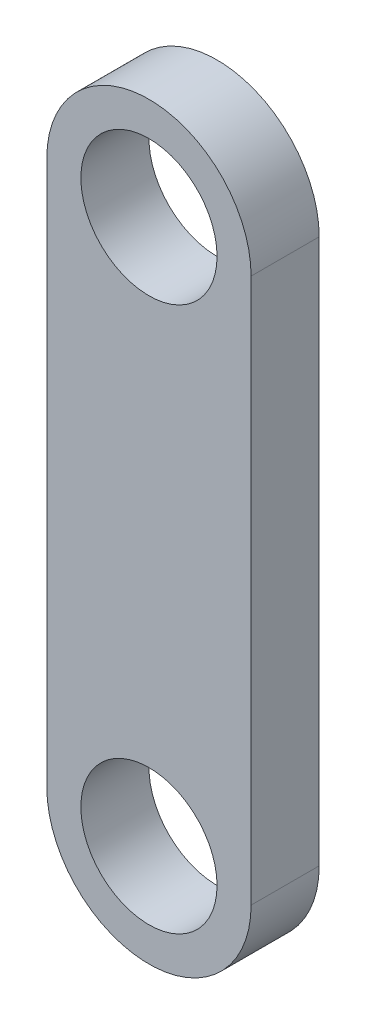
SolidWorks part; units mm, degrees
ref_plane "前视基准面" through (0, 0, 0) normal (0, 0, 1) x (1, 0, 0)
ref_plane "上视基准面" through (0, 0, 0) normal (0, 1, 0) x (1, 0, 0)
ref_plane "右视基准面" through (0, 0, 0) normal (1, 0, 0) x (0, 0, -1)
other "Configuration Table"
sketch "草图1" plane through (0, 0, 0) normal (0, 0, 1) x (1, 0, 0)
  line L0 (0, 0) -> (0, 40) construction
  line L1 (-7.5, 0) -> (-7.5, 40)
  line L2 (7.5, 0) -> (7.5, 40)
  arc A0 (-7.5, 0) -> (7.5, 0) centre (0, 0) ccw
  arc A1 (7.5, 40) -> (-7.5, 40) centre (0, 40) ccw
  point P3 (0, 20)
  dimension "D1" = 7.5
  dimension "D2" = 40
extrude "凸台-拉伸1" add sketch "草图1" along normal blind 5
sketch "草图2" plane through (0, 0, 5) normal (0, 0, 1) x (1, 0, 0)
  circle A0 centre (0, 40) radius 5
  circle A1 centre (0, 0) radius 5
  dimension "D1" = 10
extrude "切除-拉伸1" cut sketch "草图2" against normal through all
